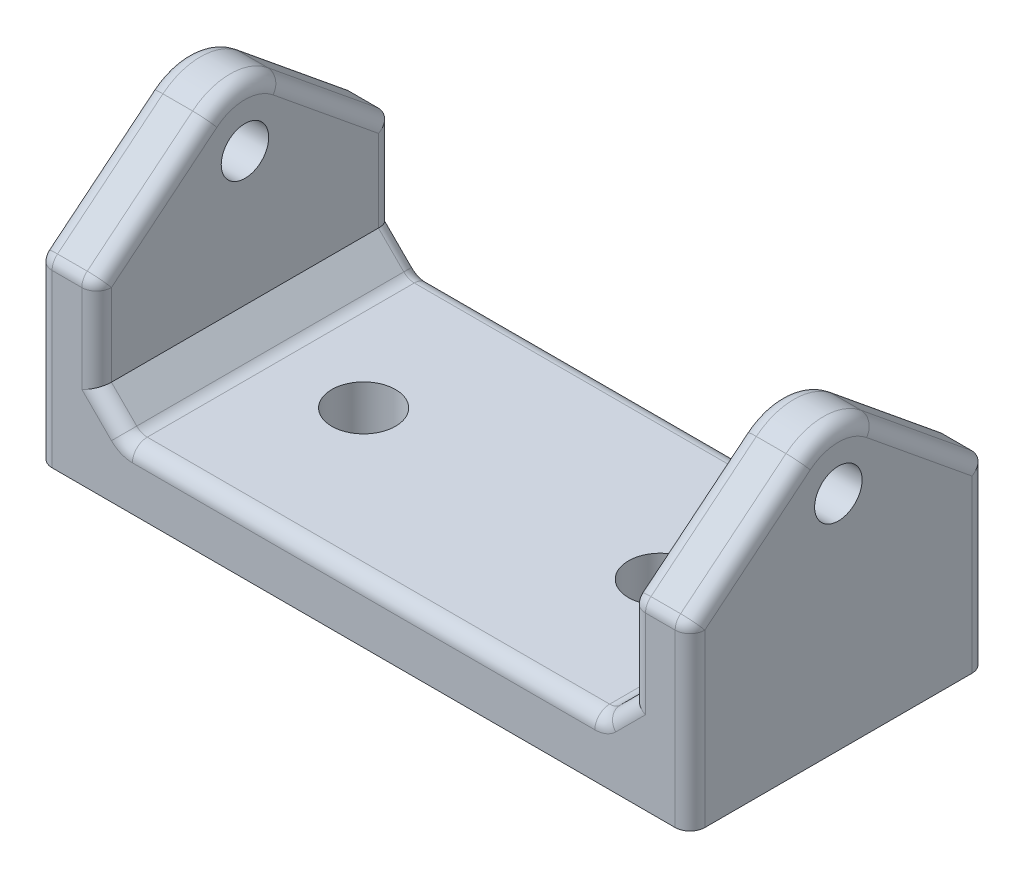
SolidWorks part; units mm, degrees
ref_plane "Front Plane" through (0, 0, 0) normal (0, 0, 1) x (1, 0, 0)
ref_plane "Top Plane" through (0, 0, 0) normal (0, 1, 0) x (1, 0, 0)
ref_plane "Right Plane" through (0, 0, 0) normal (1, 0, 0) x (0, 0, -1)
sketch "Sketch1" plane through (0, 0, 0) normal (1, 0, 0) x (0, 0, -1)
  line L0 (-10, 6) -> (-2.5296, 12.0986)
  line L1 (-10, -6) -> (10, -6)
  line L2 (-10, -6) -> (-10, 6)
  line L3 (-10, 6) -> (10, 6)
  line L4 (10, -6) -> (10, 6)
  line L5 (-10, -6) -> (10, 6) construction
  line L6 (-10, 6) -> (10, -6) construction
  line L7 (10, 6) -> (2.5296, 12.0986)
  line L8 (0, 9) -> (0, 6) construction
  arc A0 (-2.5296, 12.0986) -> (2.5296, 12.0986) centre (0, 9) cw
  circle A1 centre (0, 9) radius 1.6
  point P0 (0, 0)
  dimension "D2" = 3.2
  dimension "D4" = 4
  dimension "D1" = 12
  dimension "D3" = 20
  dimension "D5" = 3
extrude "Boss-Extrude1" add sketch "Sketch1" along normal blind 44 contours L1 L4 L3 L2 | A0 L0 L3 L7 A1
sketch "Sketch2" plane through (0, 0, 10) normal (0, 0, 1) x (1, 0, 0)
  line L0 (44, 13) -> (0, 13) construction
  line L1 (4, -2) -> (40, -2)
  line L2 (4, -2) -> (4, 13)
  line L3 (4, 13) -> (40, 13)
  line L4 (40, -2) -> (40, 13)
  line L5 (0, 13) -> (4, 13) construction
  line L6 (40, 13) -> (44, 13) construction
  line L7 (44, -6) -> (0, -6) construction
  dimension "D1" = 4
  dimension "D2" = 4
extrude "Cut-Extrude1" cut sketch "Sketch2" against normal through all
chamfer "Chamfer1" distance 2 angle 45 2 edges at (40, -2, 0) (4, -2, 0)
fillet "Fillet1" radius 1 30 edges at (40, 3, -10) (40, 3, 10) (4, 3, -10) (4, 3, 10) (0, 0, -10) (44, 0, -10) (44, 0, 10) (0, 0, 10) (44, 9.0493, -6.2648) (44, 13, 0) (40, 9.0493, -6.2648) (40, 13, 0) (0, 9.0493, -6.2648) (0, 13, 0) (4, 9.0493, -6.2648) (4, 13, 0) (44, 9.0493, 6.2648) (42, 6, 10) (40, 9.0493, 6.2648) (2, 6, 10) (0, 9.0493, 6.2648) (4, 9.0493, 6.2648) (5, -1, -10) (5, -1, 10) (39, -1, -10) (39, -1, 10) (6, -2, 0) (22, -2, -10) (38, -2, 0) (22, -2, 10)
sketch "Sketch3" plane through (0, -2, 0) normal (0, 1, 0) x (1, 0, 0)
  line L0 (22, 10) -> (22, -10) construction
  line L1 (6.4142, 10) -> (37.5858, 10) construction
  line L2 (37.5858, -10) -> (6.4142, -10) construction
  line L3 (12, 0) -> (32, 0)
  circle A0 centre (12, 0) radius 2.15
  circle A1 centre (32, 0) radius 2.15
  point P2 (15.1992, 0)
  point P10 (29.3996, 0)
  point P14 (22, 0)
  dimension "D1" = 4.3
  dimension "D2" = 20
extrude "Cut-Extrude2" cut sketch "Sketch3" against normal through all
